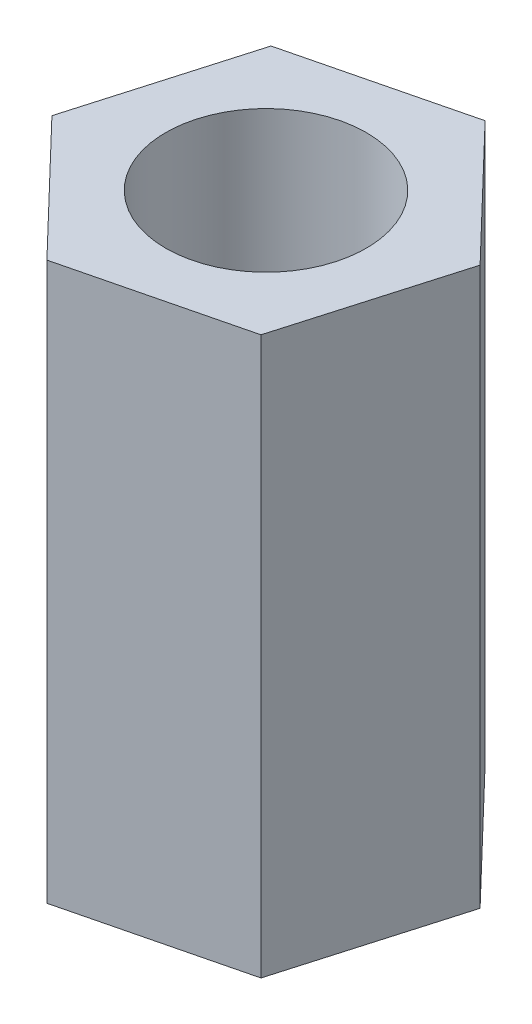
SolidWorks part; units mm, degrees
ref_plane "Front Plane" through (0, 0, 0) normal (0, 0, 1) x (1, 0, 0)
ref_plane "Top Plane" through (0, 0, 0) normal (0, 1, 0) x (1, 0, 0)
ref_plane "Right Plane" through (0, 0, 0) normal (1, 0, 0) x (0, 0, -1)
sketch "Sketch1" plane through (0, 0, 0) normal (0, 1, 0) x (1, 0, 0)
  line L1 (2.1998, -2.29) -> (3.0831, 0.7601)
  line L2 (3.0831, 0.7601) -> (0.8833, 3.0501)
  line L3 (0.8833, 3.0501) -> (-2.1998, 2.29)
  line L4 (-2.1998, 2.29) -> (-3.0831, -0.7601)
  line L5 (-3.0831, -0.7601) -> (-0.8833, -3.0501)
  line L6 (-0.8833, -3.0501) -> (2.1998, -2.29)
  circle A0 centre (0, 0) radius 2.75 construction
  circle A1 centre (0, 0) radius 1.8
  dimension "D1" = 5.5
  dimension "D2" = 3.6
extrude "Boss-Extrude1" add sketch "Sketch1" along normal blind 10
